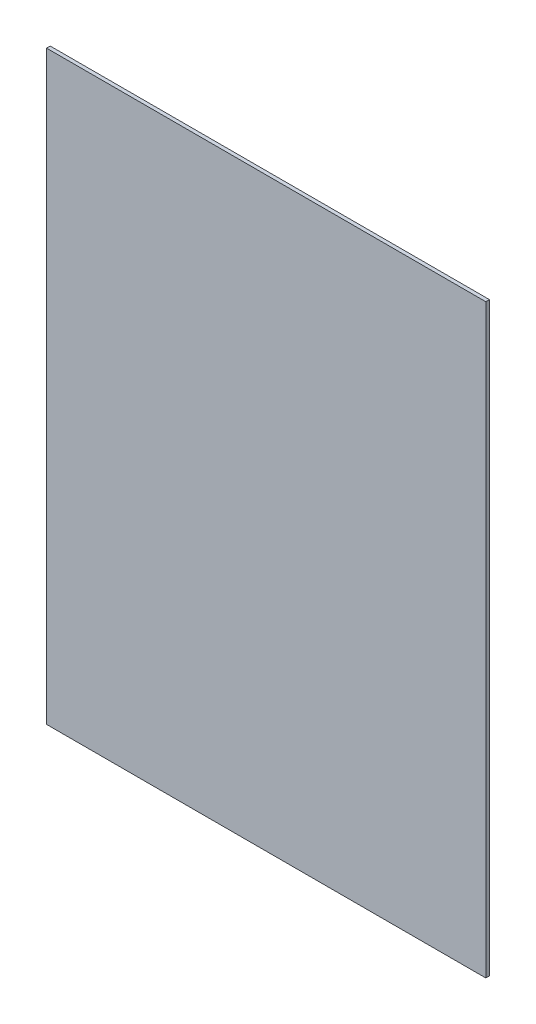
SolidWorks part; units mm, degrees
ref_plane "Plan de face" through (0, 0, 0) normal (0, 0, 1) x (1, 0, 0)
ref_plane "Plan de dessus" through (0, 0, 0) normal (0, 1, 0) x (1, 0, 0)
ref_plane "Plan de droite" through (0, 0, 0) normal (1, 0, 0) x (0, 0, -1)
sketch "Esquisse1" plane through (0, 0, 0) normal (0, 0, 1) x (1, 0, 0)
  line L1 (-300, 400) -> (300, 400)
  line L2 (-300, 400) -> (-300, -400)
  line L3 (-300, -400) -> (300, -400)
  line L4 (300, 400) -> (300, -400)
  line L5 (-300, 400) -> (300, -400) construction
  line L6 (-300, -400) -> (300, 400) construction
  point P0 (0, 0)
  dimension "D1" = 800
  dimension "D2" = 600
extrude "Boss.-Extru.1" add sketch "Esquisse1" along normal blind 5
